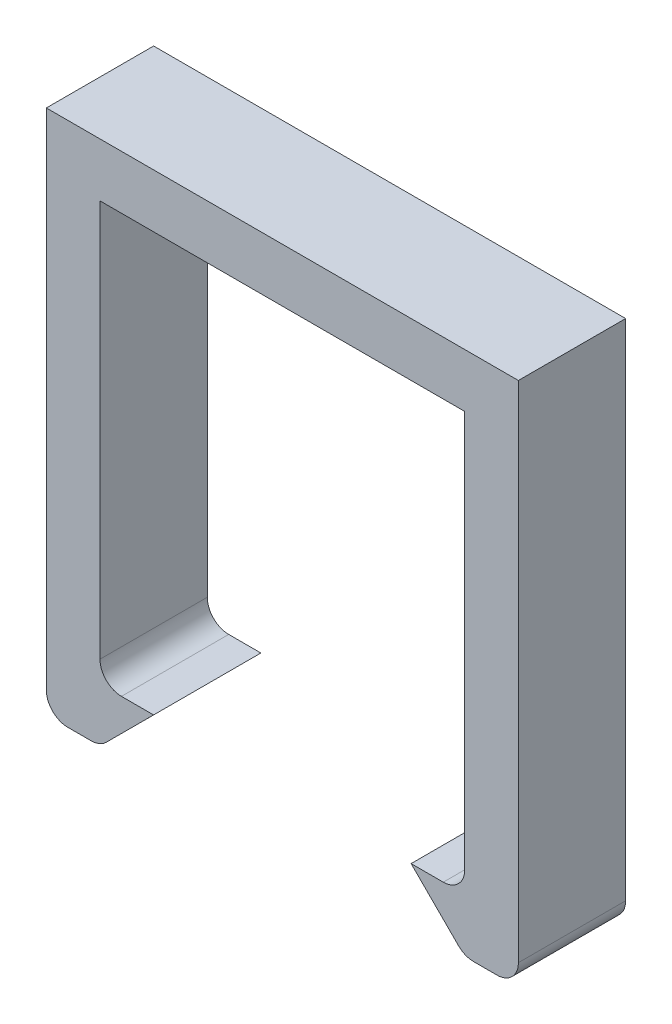
SolidWorks part; units mm, degrees
ref_plane "Front Plane" through (0, 0, 0) normal (0, 0, 1) x (1, 0, 0)
ref_plane "Top Plane" through (0, 0, 0) normal (0, 1, 0) x (1, 0, 0)
ref_plane "Right Plane" through (0, 0, 0) normal (1, 0, 0) x (0, 0, -1)
sketch "Sketch2" plane through (0, 0, 0) normal (0, 0, 1) x (1, 0, 0)
  line L0 (0, 0) -> (49.5303, 0)
  line L1 (49.5303, 0) -> (49.5303, -59.69)
  line L2 (46.9903, -62.23) -> (44.2324, -62.23)
  line L3 (43.1805, -53.34) -> (43.1805, -6.35)
  line L4 (43.1805, -6.35) -> (0, -6.35)
  line L5 (0, -6.35) -> (0, -53.34)
  line L6 (-1.0519, -62.23) -> (-3.8097, -62.23)
  line L7 (-6.3497, -59.69) -> (-6.3497, 0)
  line L8 (-6.3497, 0) -> (0, 0)
  line L9 (0.7442, -61.486) -> (6.35, -55.88)
  line L10 (6.35, -55.88) -> (2.54, -55.88)
  line L11 (21.5903, -6.35) -> (21.5903, -82.5492) construction
  line L12 (36.8305, -55.88) -> (40.6405, -55.88)
  line L13 (42.4363, -61.486) -> (36.8305, -55.88)
  arc A0 (2.54, -55.88) -> (0, -53.34) centre (2.54, -53.34) cw
  arc A1 (43.1805, -53.34) -> (40.6405, -55.88) centre (40.6405, -53.34) cw
  arc A2 (0.7442, -61.486) -> (-1.0519, -62.23) centre (-1.0519, -59.69) cw
  arc A3 (44.2324, -62.23) -> (42.4363, -61.486) centre (44.2324, -59.69) cw
  arc A4 (49.5303, -59.69) -> (46.9903, -62.23) centre (46.9903, -59.69) cw
  arc A5 (-3.8097, -62.23) -> (-6.3497, -59.69) centre (-3.8097, -59.69) cw
  point P17 (43.1926, -57.9789)
  point P19 (0, -55.88)
  point P22 (43.1805, -55.88)
  point P25 (0.0003, -62.23)
  point P28 (43.1803, -62.23)
  point P31 (49.5303, -62.23)
  point P34 (-6.3497, -62.23)
  dimension "D5" = 2.54
  dimension "D6" = 2.54
  dimension "D7" = 2.54
  dimension "D1" = 55.88
  dimension "D2" = 6.35
  dimension "D3" = 6.35
  dimension "D4" = 55.88
  dimension "D8" = 6.35
  dimension "D9" = 6.35
  dimension "D10" = 6.35
extrude "Boss-Extrude1" add sketch "Sketch2" along normal blind 12.7 contours L0 L1 A4 L2 A3 L13 L12 A1 L3 L4 L5 A0 L10 L9 A2 L6 A5 L7 L8
equation "\"modulus\"= 435000"
equation "\"safety_factor\"= 3.5"
equation "\"tensile\"= 5"
equation "\"axial\"= 7.5"
equation "\"yield\" = 7250"
equation "\"width\"= 0.5"
equation "\"base\"= 0.25"
equation "\"deflection\"= 1 / 64"
equation "\"length\"= ( ( \"deflection\" * 3 * \"modulus\" * \"base\" * \"width\" ^ 3 ) / ( 12 * \"tensile\" ) ) ^ ( 1 / 3 )"
equation "\"area\"= \"base\" * \"width\""
